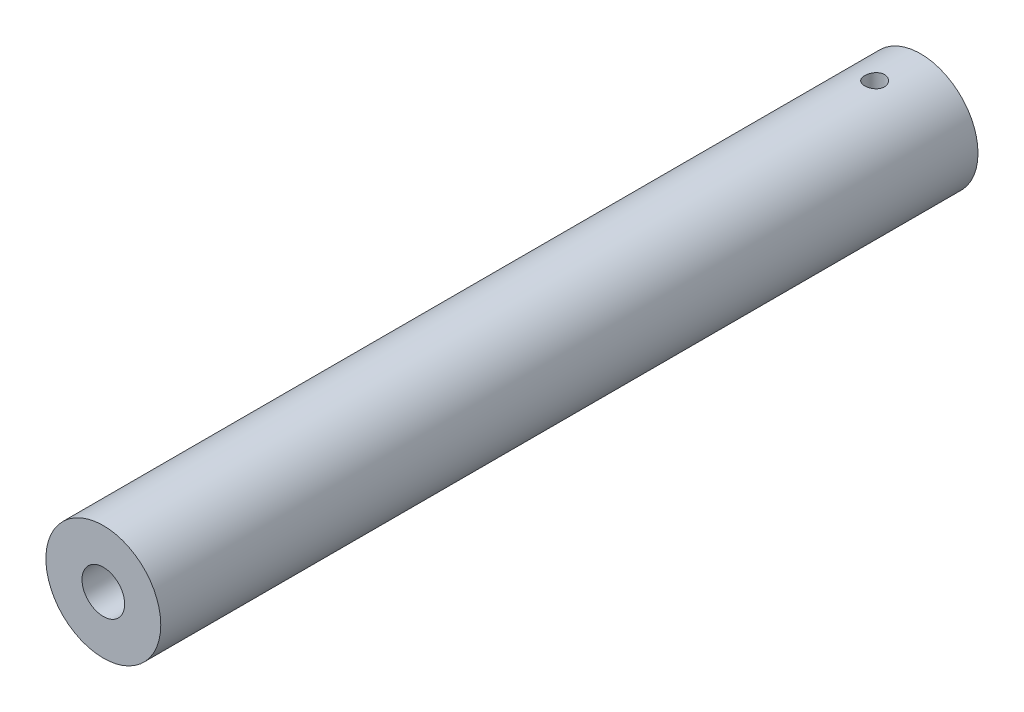
SolidWorks part; units mm, degrees
ref_plane "Front" through (0, 0, 0) normal (0, 0, 1) x (1, 0, 0)
ref_plane "Top" through (0, 0, 0) normal (0, 1, 0) x (1, 0, 0)
ref_plane "Right" through (0, 0, 0) normal (1, 0, 0) x (0, 0, -1)
sketch "Sketch1" plane through (0, 0, 0) normal (0, 0, 1) x (1, 0, 0)
  circle A0 centre (0, 0) radius 17.5
  dimension "D1" = 35
extrude "Boss-Extrude1" add sketch "Sketch1" along normal blind 249
sketch "Sketch2" plane through (0, 0, 249) normal (0, 0, 1) x (1, 0, 0)
  circle A0 centre (0, 0) radius 6.5
  dimension "D1" = 13
extrude "Cut-Extrude1" cut sketch "Sketch2" against normal blind 55
ref_plane "Plane1" through (0, 0, 237) normal (0, 0, 1) x (1, 0, 0)
sketch "Sketch3" plane through (0, 0, 237) normal (0, 0, 1) x (1, 0, 0)
  line L0 (0, 0) -> (0, 17.5)
  line L1 (0, 0) -> (-15.1554, -8.75)
  line L2 (0, 0) -> (15.1554, -8.75)
  circle A0 centre (0, 0) radius 17.5 construction
  dimension "D1" = 120
  dimension "D2" = 120
ref_plane "Plane3" through (0, 17.5, 237) normal (0, 1, 0) x (1, 0, 0)
sketch "Sketch9" plane through (0, 0, 0) normal (0, 0, -1) x (-1, 0, 0)
  circle A0 centre (0, 0) radius 10
  dimension "D1" = 20
extrude "Cut-Extrude5" cut sketch "Sketch9" against normal blind 50
sketch "Sketch10" plane through (0, 0, 0) normal (0, 1, 0) x (1, 0, 0)
  circle A0 centre (0, -14) radius 3
  dimension "D1" = 6
  dimension "D2" = 14
extrude "Cut-Extrude6" cut sketch "Sketch10" against normal through all both and the other way through all contours A0
